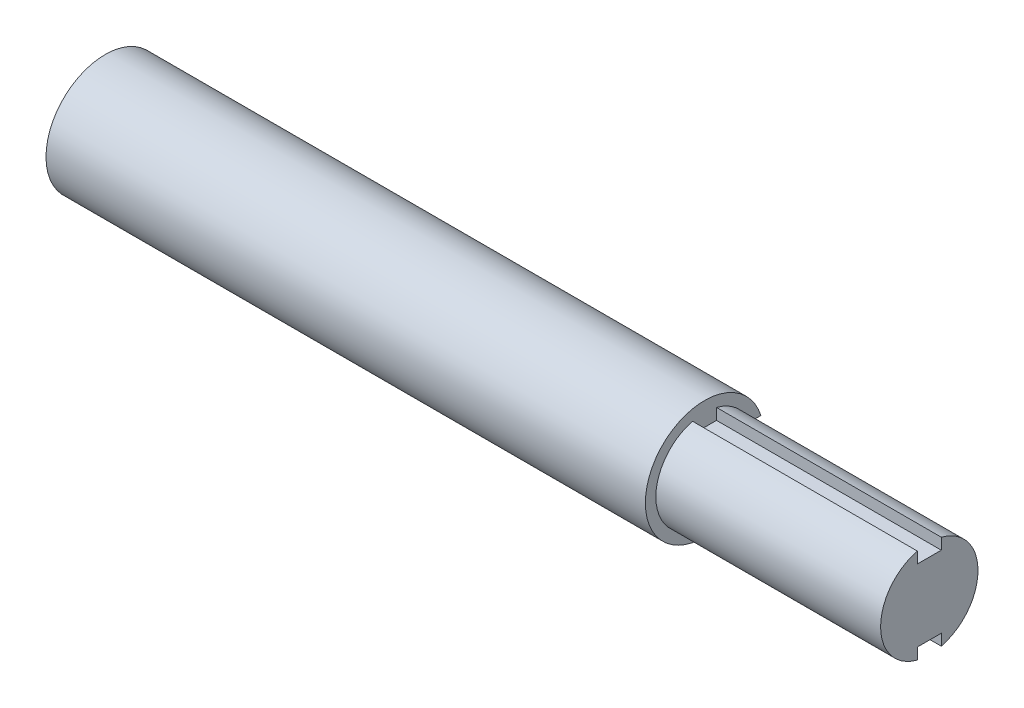
SolidWorks part; units mm, degrees
ref_plane "Front Plane" through (0, 0, 0) normal (0, 0, 1) x (1, 0, 0)
ref_plane "Top Plane" through (0, 0, 0) normal (0, 1, 0) x (1, 0, 0)
ref_plane "Right Plane" through (0, 0, 0) normal (1, 0, 0) x (0, 0, -1)
sketch "Sketch1" plane through (0, 0, 0) normal (1, 0, 0) x (0, 0, -1)
  circle A0 centre (0, 0) radius 6.5
extrude "Boss-Extrude1" add sketch "Sketch1" along normal blind 30
sketch "Sketch2" plane through (0, 0, 0) normal (-1, 0, 0) x (0, 0, 1)
  circle A0 centre (0, 0) radius 7.9
extrude "Boss-Extrude2" add sketch "Sketch2" along normal blind 80
sketch "Sketch3" plane through (30, 0, 0) normal (1, 0, 0) x (0, 0, -1)
  line L0 (0, 0) -> (0, 8.5912) construction
  line L1 (0, 0) -> (0, -8.7494) construction
  line L2 (-1.6, 6.8) -> (1.6, 6.8)
  line L3 (-1.6, 6.8) -> (-1.6, 4.8)
  line L4 (-1.6, 4.8) -> (1.6, 4.8)
  line L5 (1.6, 6.8) -> (1.6, 4.8)
  line L7 (1.6, -6.8) -> (-1.6, -6.8)
  line L8 (1.6, -6.8) -> (1.6, -4.8)
  line L9 (1.6, -4.8) -> (-1.6, -4.8)
  line L10 (-1.6, -6.8) -> (-1.6, -4.8)
  dimension "D1" = 3.2
  dimension "D2" = 2
  dimension "D3" = 3.2
  dimension "D4" = 2
extrude "Cut-Extrude2" cut sketch "Sketch3" against normal blind 30
sketch "Sketch5" plane through (-80, 0, 0) normal (-1, 0, 0) x (0, 0, 1)
  line L0 (0, 0) -> (-10.665, 0) construction
  line L2 (-8.1266, 2.4) -> (-5.1266, 2.4)
  line L3 (-8.1266, 2.4) -> (-8.1266, -2.4)
  line L4 (-8.1266, -2.4) -> (-5.1266, -2.4)
  line L5 (-5.1266, 2.4) -> (-5.1266, -2.4)
  dimension "D1" = 4.8
  dimension "D2" = 3
extrude "Cut-Extrude3" cut sketch "Sketch5" against normal blind 80
